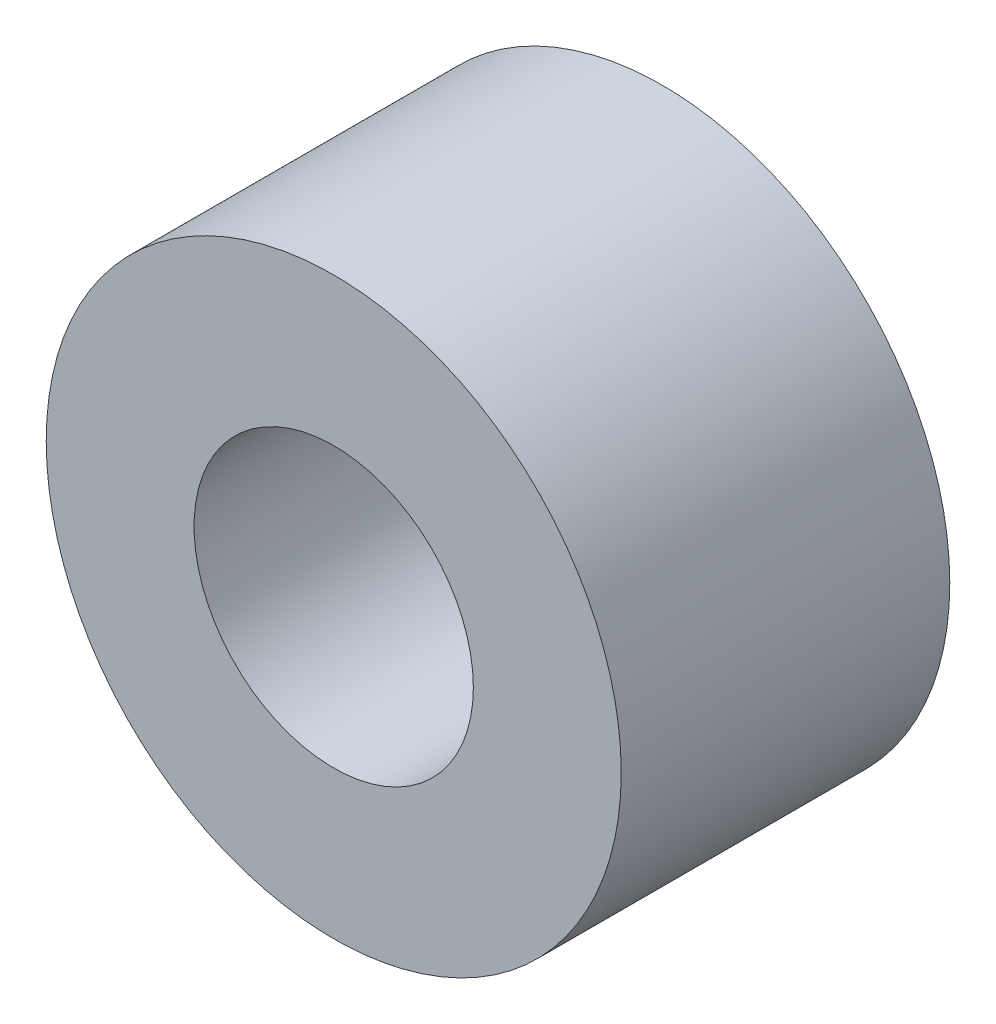
SolidWorks part; units mm, degrees
ref_plane "Front Plane" through (0, 0, 0) normal (0, 0, 1) x (1, 0, 0)
ref_plane "Top Plane" through (0, 0, 0) normal (0, 1, 0) x (1, 0, 0)
ref_plane "Right Plane" through (0, 0, 0) normal (1, 0, 0) x (0, 0, -1)
sketch "Sketch1" plane through (0, 0, 0) normal (0, 0, 1) x (1, 0, 0)
  circle A0 centre (0, 0) radius 1.7
  circle A1 centre (0, 0) radius 3.5
  dimension "D1" = 3.4
  dimension "D2" = 7
extrude "Boss-Extrude1" add sketch "Sketch1" along normal blind 4
